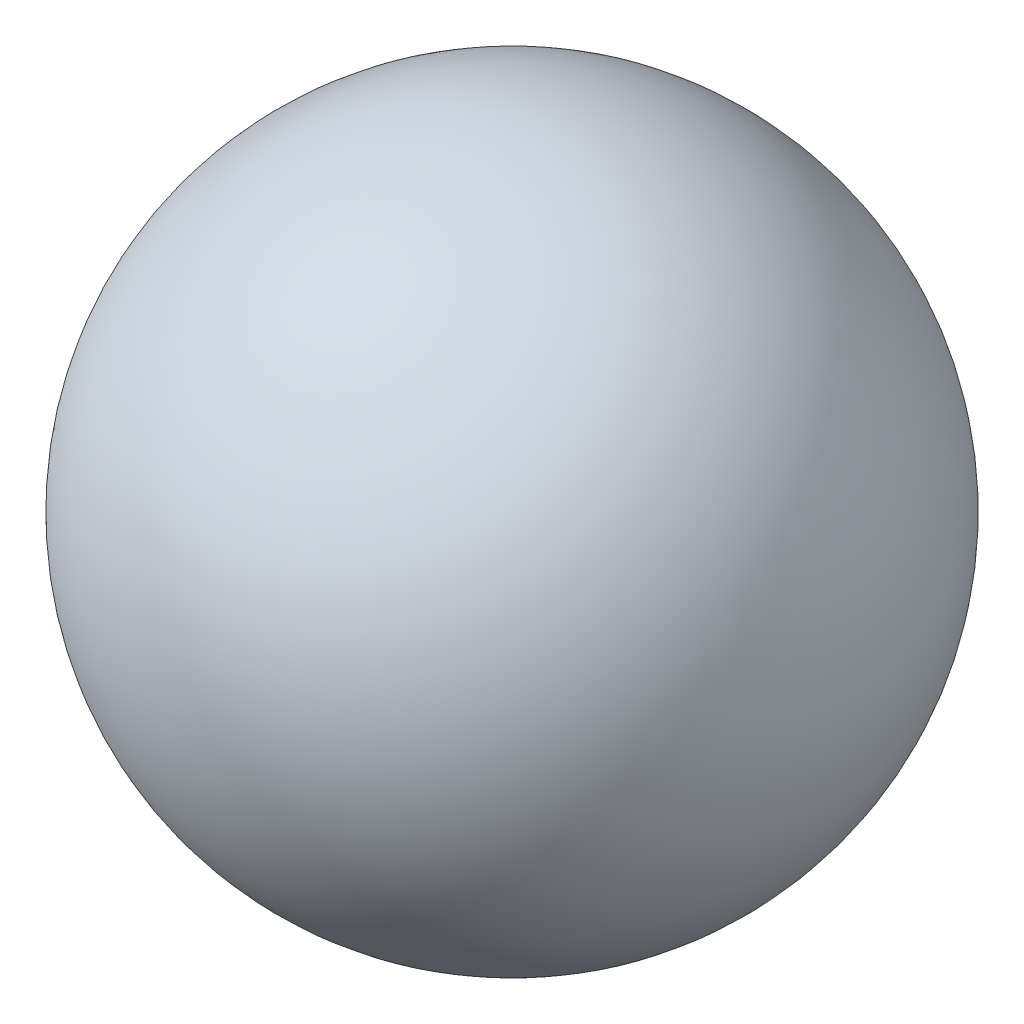
SolidWorks part; units mm, degrees
material "POLYURETHANE (11671)"
ref_plane "Front Plane" through (0, 0, 0) normal (0, 0, 1) x (1, 0, 0)
ref_plane "Top Plane" through (0, 0, 0) normal (0, 1, 0) x (1, 0, 0)
ref_plane "Right Plane" through (0, 0, 0) normal (1, 0, 0) x (0, 0, -1)
sketch "Sketch1" plane through (0, 0, 0) normal (0, 0, 1) x (1, 0, 0)
  line L0 (0, 31.5) -> (0, -31.5)
  arc A0 (0, 31.5) -> (0, -31.5) centre (0, 0) ccw
  dimension "D1" = 63
revolve "Revolve1" add sketch "Sketch1" angle 360 about L0
